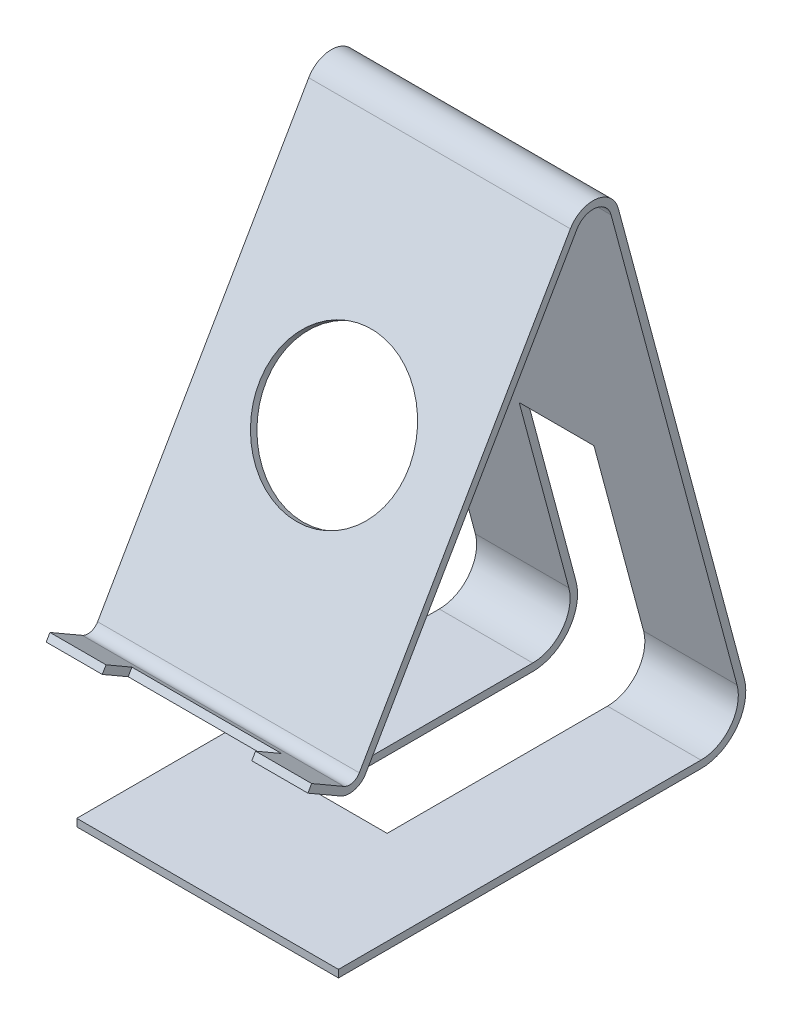
SolidWorks part; units mm, degrees
ref_plane "Front Plane" through (0, 0, 0) normal (0, 0, 1) x (1, 0, 0)
ref_plane "Top Plane" through (0, 0, 0) normal (0, 1, 0) x (1, 0, 0)
ref_plane "Right Plane" through (0, 0, 0) normal (1, 0, 0) x (0, 0, -1)
sketch "Sketch1" plane through (0, 0, 0) normal (1, 0, 0) x (0, 0, -1)
  line L0 (-38.0221, 0) -> (58.9456, 0)
  line L1 (68.6049, 12.5882) -> (34.9097, 138.3402)
  line L2 (25.75, 139.5461) -> (-30.7145, 41.7468)
  line L3 (-37.5446, 39.9167) -> (-46.2049, 44.9167)
  arc A0 (58.9456, 0) -> (68.6049, 12.5882) centre (58.9456, 10) ccw
  arc A1 (34.9097, 138.3402) -> (25.75, 139.5461) centre (30.0801, 137.0461) ccw
  arc A2 (-30.7145, 41.7468) -> (-37.5446, 39.9167) centre (-35.0446, 44.2468) cw
  point P8 (71.9779, 0)
  point P11 (31.7855, 150)
  point P14 (-33.2145, 37.4167)
  dimension "D7" = 10
  dimension "D8" = 5
  dimension "D9" = 5
  dimension "D1" = 110
  dimension "D2" = 150
  dimension "D3" = 130
  dimension "D4" = 15
  dimension "D5" = 75
  dimension "D6" = 45
extrude "Extrude-Thin1" add sketch "Sketch1" along normal blind 70 thin
sketch "Sketch2" plane through (0, 15.4123, -8.8983) normal (0, 0.866, -0.5) x (1, 0, 0)
  line L0 (70, -62.473) -> (0, -62.473) construction
  line L1 (15, -62.473) -> (55, -62.473)
  line L2 (15, -62.473) -> (15, -54.473)
  line L3 (15, -54.473) -> (55, -54.473)
  line L4 (55, -62.473) -> (55, -54.473)
  line L5 (0, -52.473) -> (0, -62.473) construction
  line L6 (70, -52.473) -> (70, -62.473) construction
  dimension "D1" = 15
  dimension "D2" = 15
  dimension "D3" = 8
extrude "Cut-Extrude1" cut sketch "Sketch2" against normal blind 10
sketch "Sketch3" plane through (0, 0, 0) normal (0, 0, 1) x (1, 0, 0)
  line L0 (0, 12.5882) -> (0, 138.3402) construction
  line L1 (25, -37.8472) -> (45, -37.8472)
  line L2 (25, -37.8472) -> (25, 62.1528)
  line L3 (25, 62.1528) -> (45, 62.1528)
  line L4 (45, -37.8472) -> (45, 62.1528)
  line L5 (70, 12.5882) -> (70, 138.3402) construction
  dimension "D1" = 20
  dimension "D2" = 100
  dimension "D3" = 25
  dimension "D4" = 25
extrude "Cut-Extrude2" cut sketch "Sketch3" against normal blind 90
sketch "Sketch9" plane through (0, 24.7365, 42.8448) normal (0, 0.5, 0.866) x (1, 0, 0)
  circle A1 centre (35, 77.261) radius 3030
  circle A3 centre (35, 77.261) radius 20
  dimension "D1" = 40
extrude "Cut-Extrude9" cut sketch "Sketch9" against normal blind 2 contours A3
